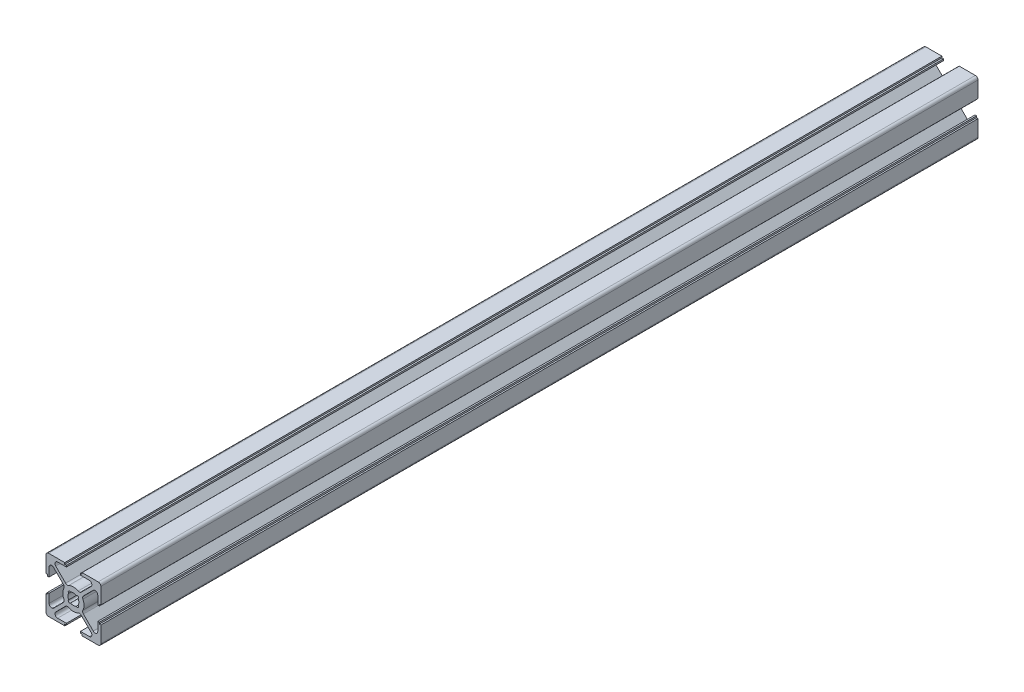
SolidWorks part; units mm, degrees
ref_plane "Ön Düzlem" through (0, 0, 0) normal (0, 0, 1) x (1, 0, 0)
ref_plane "Üst Düzlem" through (0, 0, 0) normal (0, 1, 0) x (1, 0, 0)
ref_plane "Sağ Düzlem" through (0, 0, 0) normal (1, 0, 0) x (0, 0, -1)
sketch "Çizim1" plane through (0, 0, 0) normal (0, 0, 1) x (1, 0, 0)
  line L0 (3.95, 12.5) -> (11.3, 12.5)
  line L1 (-11.3, 12.5) -> (-3.95, 12.5)
  line L2 (-12.5, 11.3) -> (-12.5, 3.95)
  line L3 (-11.3, -12.5) -> (-3.95, -12.5)
  line L4 (12.5, 11.3) -> (12.5, 3.95)
  line L5 (9.0515, 8.0615) -> (4.5565, 3.5666)
  line L6 (8.0615, -9.0515) -> (3.5666, -4.5565)
  line L7 (-7.213, 11.1) -> (-3.2, 11.1)
  line L9 (-7.213, -11.1) -> (-3.2, -11.1)
  line L10 (11.1, 7.213) -> (11.1, 3.2)
  line L11 (9.0515, -8.0615) -> (4.5565, -3.5666)
  line L12 (-9.0515, -8.0615) -> (-4.5565, -3.5666)
  line L14 (11.8, -3.2) -> (11.1, -3.2)
  line L16 (11.1, 3.2) -> (11.8, 3.2)
  line L17 (11.1, -3.2) -> (11.1, -7.213)
  line L18 (12.5, -3.95) -> (12.5, -11.3)
  line L19 (11.8, 3.2) -> (11.8, 3.95)
  line L20 (11.8, 3.95) -> (12.5, 3.95)
  line L21 (11.8, -3.2) -> (11.8, -3.95)
  line L22 (11.8, -3.95) -> (12.5, -3.95)
  line L24 (-3.2, 11.8) -> (-3.2, 11.1)
  line L26 (3.2, 11.1) -> (3.2, 11.8)
  line L28 (3.2, 11.1) -> (7.213, 11.1)
  line L29 (-3.2, 11.8) -> (-3.95, 11.8)
  line L30 (-3.95, 11.8) -> (-3.95, 12.5)
  line L31 (3.2, 11.8) -> (3.95, 11.8)
  line L32 (3.95, 11.8) -> (3.95, 12.5)
  line L33 (-12.5, -3.95) -> (-12.5, -11.3)
  line L34 (-11.1, -3.2) -> (-11.1, -7.213)
  line L35 (3.2, -11.1) -> (3.2, -11.8)
  line L36 (3.2, -11.8) -> (3.95, -11.8)
  line L37 (3.95, -11.8) -> (3.95, -12.5)
  line L38 (-3.95, -11.8) -> (-3.95, -12.5)
  line L39 (-3.2, -11.8) -> (-3.95, -11.8)
  line L40 (-3.2, -11.8) -> (-3.2, -11.1)
  line L41 (3.95, -12.5) -> (11.3, -12.5)
  line L42 (3.2, -11.1) -> (7.213, -11.1)
  line L43 (-11.8, 3.95) -> (-12.5, 3.95)
  line L44 (-11.8, 3.2) -> (-11.8, 3.95)
  line L45 (-11.1, 3.2) -> (-11.8, 3.2)
  line L46 (-11.8, -3.95) -> (-12.5, -3.95)
  line L47 (-11.8, -3.2) -> (-11.8, -3.95)
  line L48 (-11.8, -3.2) -> (-11.1, -3.2)
  line L49 (-11.1, 7.213) -> (-11.1, 3.2)
  line L50 (-8.0615, -9.0515) -> (-3.5666, -4.5565)
  line L51 (8.0615, 9.0515) -> (3.5666, 4.5565)
  line L52 (-8.0615, 9.0515) -> (-3.5666, 4.5565)
  line L53 (-9.0515, 8.0615) -> (-4.5565, 3.5666)
  arc A0 (1.2957, 2.1381) -> (-1.2957, 2.1381) centre (0, 0) ccw
  arc A1 (2.1789, 4.333) -> (-2.1789, 4.333) centre (0, 0) ccw
  arc A2 (4.333, -2.1789) -> (4.333, 2.1789) centre (0, 0) ccw
  arc A3 (-2.1789, -4.333) -> (2.1789, -4.333) centre (0, 0) ccw
  arc A4 (-4.333, 2.1789) -> (-4.333, -2.1789) centre (0, 0) ccw
  arc A5 (-7.213, 11.1) -> (-8.0615, 9.0515) centre (-7.213, 9.9) ccw
  arc A6 (-9.0515, 8.0615) -> (-11.1, 7.213) centre (-9.9, 7.213) ccw
  arc A7 (-4.333, 2.1789) -> (-4.5565, 3.5666) centre (-5.4051, 2.7181) ccw
  arc A8 (-3.5666, 4.5565) -> (-2.1789, 4.333) centre (-2.7181, 5.4051) ccw
  arc A9 (2.1789, 4.333) -> (3.5666, 4.5565) centre (2.7181, 5.4051) ccw
  arc A10 (4.333, 2.1789) -> (4.5565, 3.5666) centre (5.4051, 2.7181) cw
  arc A11 (4.333, -2.1789) -> (4.5565, -3.5666) centre (5.4051, -2.7181) ccw
  arc A12 (3.5666, -4.5565) -> (2.1789, -4.333) centre (2.7181, -5.4051) ccw
  arc A13 (-2.1789, -4.333) -> (-3.5666, -4.5565) centre (-2.7181, -5.4051) ccw
  arc A14 (-4.333, -2.1789) -> (-4.5565, -3.5666) centre (-5.4051, -2.7181) cw
  arc A15 (-11.1, -7.213) -> (-9.0515, -8.0615) centre (-9.9, -7.213) ccw
  arc A16 (-8.0615, -9.0515) -> (-7.213, -11.1) centre (-7.213, -9.9) ccw
  arc A17 (7.213, -11.1) -> (8.0615, -9.0515) centre (7.213, -9.9) ccw
  arc A18 (11.1, -7.213) -> (9.0515, -8.0615) centre (9.9, -7.213) cw
  arc A19 (9.0515, 8.0615) -> (11.1, 7.213) centre (9.9, 7.213) cw
  arc A20 (7.213, 11.1) -> (8.0615, 9.0515) centre (7.213, 9.9) cw
  arc A21 (11.3, 12.5) -> (12.5, 11.3) centre (11.3, 11.3) cw
  arc A22 (12.5, -11.3) -> (11.3, -12.5) centre (11.3, -11.3) cw
  arc A23 (-11.3, -12.5) -> (-12.5, -11.3) centre (-11.3, -11.3) cw
  arc A24 (-12.5, 11.3) -> (-11.3, 12.5) centre (-11.3, 11.3) cw
  arc A25 (2.1381, 1.2957) -> (1.2957, 2.1381) centre (1.7678, 1.7678) ccw
  arc A26 (1.2957, -2.1381) -> (2.1381, -1.2957) centre (1.7678, -1.7678) ccw
  arc A27 (-2.1381, -1.2957) -> (-1.2957, -2.1381) centre (-1.7678, -1.7678) ccw
  arc A28 (-1.2957, 2.1381) -> (-2.1381, 1.2957) centre (-1.7678, 1.7678) ccw
  arc A29 (-2.1381, 1.2957) -> (-2.1381, -1.2957) centre (0, 0) ccw
  arc A30 (-1.2957, -2.1381) -> (1.2957, -2.1381) centre (0, 0) ccw
  arc A31 (2.1381, -1.2957) -> (2.1381, 1.2957) centre (0, 0) ccw
  point P0 (0, 0)
  point P5 (0, 0)
  point P52 (5.055, 6.045)
  point P55 (6.045, -5.055)
  point P61 (-5.055, -6.045)
  point P66 (-6.045, 5.055)
  point P68 (0, 0)
  point P117 (0, 0)
  dimension "D1" = 4
  dimension "D2" = 1.2
  dimension "D3" = 4
extrude "Yükseklik-Ekstrüzyon1" add sketch "Çizim1" along normal blind 400
